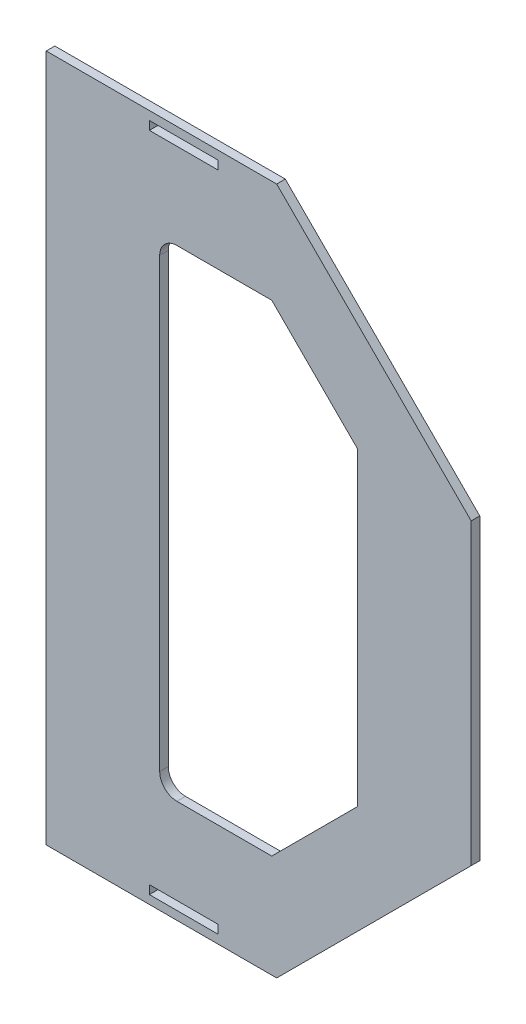
SolidWorks part; units mm, degrees
material "AISI 1020 Steel, Cold Rolled"
ref_plane "Front Plane" through (0, 0, 0) normal (0, 0, 1) x (1, 0, 0)
ref_plane "Top Plane" through (0, 0, 0) normal (0, 1, 0) x (1, 0, 0)
ref_plane "Right Plane" through (0, 0, 0) normal (1, 0, 0) x (0, 0, -1)
sketch "Sketch1" plane through (0, 0, 0) normal (0, 0, 1) x (1, 0, 0)
  line L0 (-78.486, 0) -> (78.486, 0) construction
  line L1 (-78.486, 127) -> (6.644, 127)
  line L2 (-78.486, 127) -> (-78.486, -127)
  line L3 (-78.486, -127) -> (6.644, -127)
  line L4 (78.486, 127) -> (78.486, -127) construction
  line L5 (-78.486, 127) -> (78.486, -127) construction
  line L6 (-78.486, -127) -> (78.486, 127) construction
  line L7 (-40.386, 123.825) -> (-14.986, 123.825)
  line L8 (-40.386, 123.825) -> (-40.386, 120.65)
  line L9 (-40.386, 120.65) -> (-14.986, 120.65)
  line L10 (-14.986, 123.825) -> (-14.986, 120.65)
  line L11 (-40.386, 123.825) -> (-14.986, 120.65) construction
  line L12 (-40.386, 120.65) -> (-14.986, 123.825) construction
  line L13 (-40.386, -123.825) -> (-40.386, -120.65)
  line L14 (-40.386, -123.825) -> (-14.986, -123.825)
  line L15 (-40.386, -120.65) -> (-14.986, -120.65)
  line L16 (-14.986, -123.825) -> (-14.986, -120.65)
  line L17 (6.644, 127) -> (78.486, 55.158)
  line L18 (6.644, -127) -> (78.486, -55.158)
  line L19 (78.486, -55.158) -> (78.486, 55.158)
  point P0 (0, 0)
  point P6 (-27.686, 122.2375)
  dimension "D1" = 254
  dimension "D2" = 156.972
  dimension "D3" = 3.175
  dimension "D4" = 25.4
  dimension "D5" = 3.175
  dimension "D6" = 38.1
  dimension "D7" = 45
  dimension "D8" = 101.6
extrude "Plate" add sketch "Sketch1" along normal mid plane 3.175
sketch "Sketch2" plane through (0, 0, 1.5875) normal (0, 0, 1) x (1, 0, 0)
  circle A0 centre (-50.1631, 36.7771) radius 12.5714
  circle A1 centre (8.6399, 36.7771) radius 8.7941
  circle A2 centre (38.5581, 4.7898) radius 23.4496
  circle A3 centre (-8.8952, -27.2522) radius 28.1313
  circle A4 centre (-45.2595, -45.3479) radius 11.0391
  circle A5 centre (-62.7345, -6.95) radius 6.95
  circle A6 centre (45.6874, -68.7287) radius 11.8705
  circle A7 centre (45.6874, -45.3479) radius 6.608
  circle A8 centre (4.6979, -68.7287) radius 12.034
extrude "Speed Holes" [suppressed] cut sketch "Sketch2" against normal through all
sketch "Sketch3" plane through (0, 0, -1.5875) normal (0, 0, -1) x (-1, 0, 0)
  line L1 (-6.644, 127) -> (78.486, 127) construction
  line L2 (78.486, -127) -> (-6.644, -127) construction
  line L3 (-65.786, -127) -> (-65.786, 127)
  line L4 (64.516, 127) -> (64.516, -127)
  line L5 (51.816, 127) -> (51.816, -127)
  line L6 (78.486, 127) -> (78.486, -127) construction
  line L7 (-78.486, -55.158) -> (-78.486, 55.158) construction
  dimension "D1" = 12.7
  dimension "D3" = 13.97
  dimension "D4" = 12.7
split line "Split Line1"
sketch "Sketch4" plane through (0, 0, 1.5875) normal (0, 0, 1) x (1, 0, 0)
  line L0 (4.826, 88.9) -> (36.576, 57.15)
  line L1 (-30.226, -88.9) -> (4.826, -88.9)
  line L2 (-36.576, -82.55) -> (-36.576, 82.55)
  line L3 (-30.226, 88.9) -> (4.826, 88.9)
  line L4 (36.576, -57.15) -> (36.576, 57.15)
  line L5 (-36.576, -88.9) -> (36.576, 88.9) construction
  line L6 (-36.576, 88.9) -> (36.576, -88.9) construction
  line L7 (78.486, 0) -> (-36.576, 0) construction
  line L8 (65.786, 67.858) -> (6.644, 127) construction
  line L9 (4.826, -88.9) -> (36.576, -57.15)
  line L10 (78.486, -55.158) -> (78.486, 55.158) construction
  arc A1 (-30.226, -88.9) -> (-36.576, -82.55) centre (-30.226, -82.55) cw
  arc A3 (-36.576, 82.55) -> (-30.226, 88.9) centre (-30.226, 82.55) cw
  point P0 (0, 0)
  dimension "D1" = 114.3
  dimension "D2" = 44.9013
  dimension "D3" = 165.1
  dimension "D4" = 41.91
extrude "Center Hole" cut sketch "Sketch4" against normal through all
